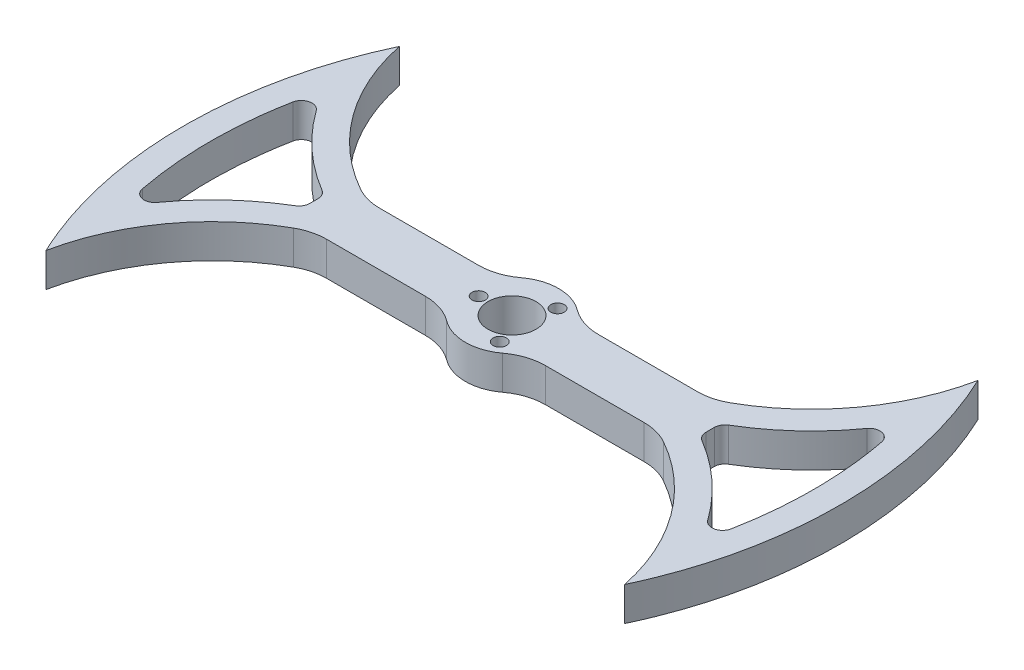
SolidWorks part; units mm, degrees
ref_plane "Front Plane" through (0, 0, 0) normal (0, 0, 1) x (1, 0, 0)
ref_plane "Top Plane" through (0, 0, 0) normal (0, 1, 0) x (1, 0, 0)
ref_plane "Right Plane" through (0, 0, 0) normal (1, 0, 0) x (0, 0, -1)
sketch "Sketch1" plane through (0, 0, 0) normal (0, 1, 0) x (1, 0, 0)
  line L0 (0, 0) -> (-80.6218, 0) construction
  line L1 (0, -18.7196) -> (0, 22.1494) construction
  line L2 (-7.1685, 5) -> (-32.1685, 5)
  line L3 (-7.1685, -5) -> (-32.1685, -5)
  line L4 (7.1685, -5) -> (32.1685, -5)
  line L5 (7.1685, 5) -> (32.1685, 5)
  circle A0 centre (0, 0) radius 8.74
  arc A1 (-54.1873, 33.1059) -> (-32.1685, 5) centre (-15, 41.1281) ccw
  arc A2 (-54.1873, -33.1059) -> (-32.1685, -5) centre (-15, -41.1281) cw
  arc A3 (54.1873, -33.1059) -> (32.1685, -5) centre (15, -41.1281) ccw
  arc A4 (54.1873, 33.1059) -> (32.1685, 5) centre (15, 41.1281) cw
  ellipse E0 centre (0, 0) end of major axis (0, 70) minor radius 61.5 (-54.1873, 33.1059) -> (-54.1873, -33.1059) ccw
  ellipse E1 centre (0, 0) end of major axis (0, 70) minor radius 61.5 (54.1873, 33.1059) -> (54.1873, -33.1059) cw
  dimension "D1" = 17.48
  dimension "D6" = 40
  dimension "D2" = 123
  dimension "D3" = 140
  dimension "D4" = 25
  dimension "D5" = 5
  dimension "D7" = 15
extrude "Boss-Extrude2" add sketch "Sketch1" along normal blind 6.35 contours A1 E0 A2 L3 A0 L2 | A0 | E1 A4 L5 A0 L4 A3
fillet "Fillet1" radius 10 8 edges at (-32.1685, 3.175, -5) (-7.1685, 3.175, -5) (7.1685, 3.175, -5) (32.1685, 3.175, -5) (32.1685, 3.175, 5) (7.1685, 3.175, 5) (-7.1685, 3.175, 5) (-32.1685, 3.175, 5)
sketch "Sketch2" plane through (0, 6.35, 0) normal (0, 1, 0) x (1, 0, 0)
  circle A0 centre (0, 0) radius 4.5
  dimension "D1" = 9
extrude "Cut-Extrude1" cut sketch "Sketch2" against normal through all
sketch "Sketch3" plane through (0, 6.35, 0) normal (0, 1, 0) x (1, 0, 0)
  line L0 (0, 0) -> (-20.3842, 0) construction
  circle A3 centre (-6.2464, 0) radius 1.25
  circle A4 centre (3.1232, 5.4095) radius 1.25
  circle A5 centre (3.1232, -5.4095) radius 1.25
  point P13 (0, 0)
  dimension "D1" = 2.5
  dimension "D3" = 3
  dimension "D2" = 6.2464
extrude "Cut-Extrude2" cut sketch "Sketch3" against normal through all
sketch "Sketch4" plane through (0, 6.35, 0) normal (0, 1, 0) x (1, 0, 0)
  line L1 (0, 0) -> (-30.9525, 0) construction
  line L2 (0, -12.2406) -> (0, 13.8155) construction
  line L5 (-37.1127, 1.9359) -> (-37.1127, -1.9359)
  line L6 (37.1127, 1.9359) -> (37.1127, -1.9359)
  arc A5 (37.1127, -1.9359) -> (54.0782, -18.8145) centre (15, -41.1281) cw
  arc A6 (54.0782, 18.8145) -> (37.1127, 1.9359) centre (15, 41.1281) cw
  arc A7 (-37.1127, -1.9359) -> (-54.0782, -18.8145) centre (-15, -41.1281) ccw
  arc A8 (-54.0782, 18.8145) -> (-37.1127, 1.9359) centre (-15, 41.1281) ccw
  arc A9 (-37.1127, -1.9359) -> (-54.0782, -18.8145) centre (-15, -41.1281) ccw
  arc A10 (-54.0782, 18.8145) -> (-37.1127, 1.9359) centre (-15, 41.1281) ccw
  circle A15 centre (0, 0) radius 8.74
  spline S0 degree 3 poles (559.7281, 2880.8796) (387.2277, -221.3036) (-37.6795, -150.9444) (-56.2961, -6.365) (-56.5, -3.1825) (-56.5, 3.1825) (-56.2961, 6.365) (-37.6796, 150.9436) (387.2229, 221.3028) (559.7252, -2880.8269) knots -10.984292 -10.984292 -10.984292 -10.984292 0.25 0.25 0.5 0.5 0.75 0.75 11.984229 11.984229 11.984229 11.984229 only from (-54.0782, -18.8145) to (-54.0782, 18.8145)
  spline S1 degree 3 poles (-54.0782, -18.8145) (-54.879, -15.7718) (-55.4856, -12.6596) (-56.2961, -6.365) (-56.5, -3.1825) (-56.5, 3.1825) (-56.2961, 6.365) (-55.4856, 12.6596) (-54.879, 15.7718) (-54.0782, 18.8145) knots 0 0 0 0 0.25 0.25 0.5 0.5 0.75 0.75 1 1 1 1
  spline S2 degree 3 poles (54.0782, -18.8145) (54.879, -15.7718) (55.4856, -12.6596) (56.2961, -6.365) (56.5, -3.1825) (56.5, 3.1825) (56.2961, 6.365) (55.4856, 12.6596) (54.879, 15.7718) (54.0782, 18.8145) knots 0 0 0 0 0.25 0.25 0.5 0.5 0.75 0.75 1 1 1 1
  dimension "D2" = 17.48
  dimension "D1" = 5
extrude "Cut-Extrude5" cut sketch "Sketch4" against normal through all contours S1 A9 L5 A10 | A5 S2 A6 L6
fillet "Fillet2" radius 2 4 edges at (-37.1127, 3.175, 1.9359) (-37.1127, 3.175, -1.9359) (-54.0782, 3.175, 18.8145) (-54.0782, 3.175, -18.8145)
fillet "Fillet3" radius 2 4 edges at (54.0782, 3.175, 18.8145) (54.0782, 3.175, -18.8145) (37.1127, 3.175, -1.9359) (37.1127, 3.175, 1.9359)
